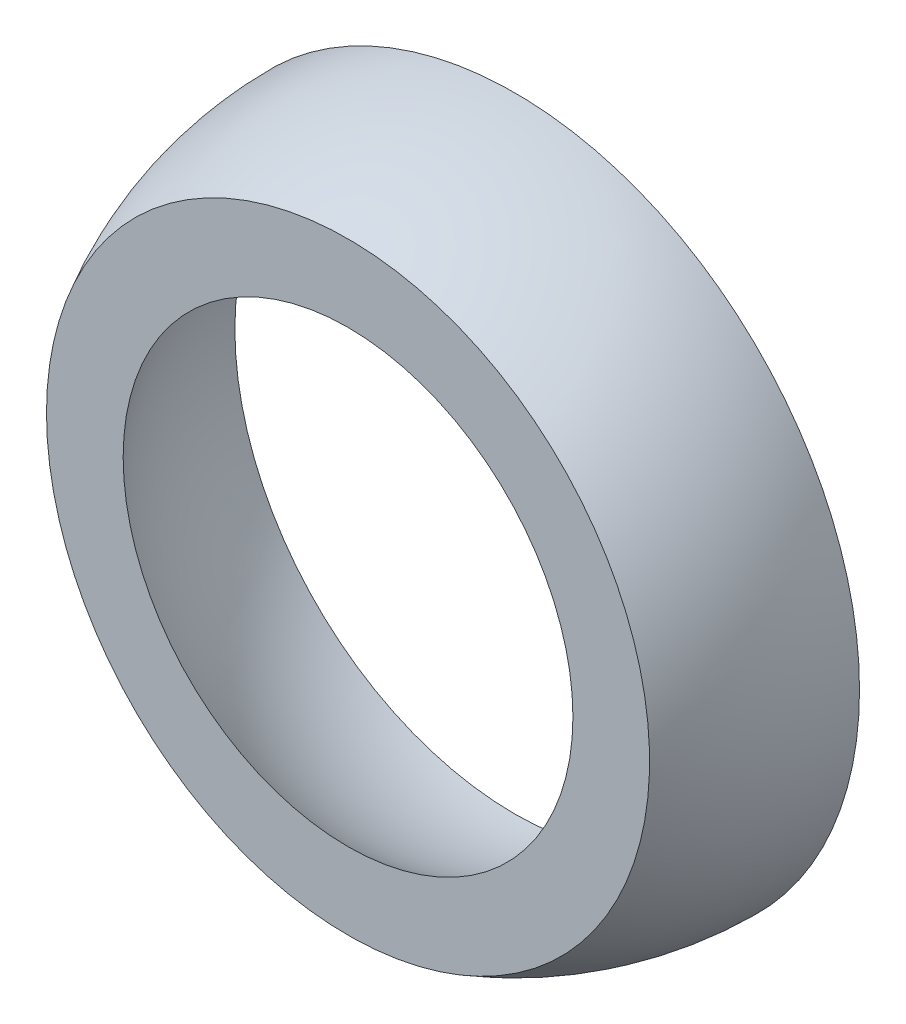
SolidWorks part; units mm, degrees
ref_plane "Plano frontal" through (0, 0, 0) normal (0, 0, 1) x (1, 0, 0)
ref_plane "Plano superior" through (0, 0, 0) normal (0, 1, 0) x (1, 0, 0)
ref_plane "Plano direito" through (0, 0, 0) normal (1, 0, 0) x (0, 0, -1)
sketch "Esboço1" plane through (0, 0, 0) normal (1, 0, 0) x (0, 0, -1)
  line L0 (-16, 0) -> (-13, 0)
  line L2 (0, 16) -> (0, 13)
  line L3 (-13, -9.1994) -> (-13, 13.9619) construction
  arc A0 (0, 13) -> (-13, 0) centre (0, 0) ccw
  arc A1 (-16, 0) -> (0, 16) centre (0, 0) cw
  dimension "D4" = 0
  dimension "D1" = 13
  dimension "D2" = 13
  dimension "D3" = 3
revolve "Revolução1" add sketch "Esboço1" angle 360 about L0
sketch "Esboço2" plane through (0, 0, 0) normal (1, 0, 0) x (0, 0, -1)
  line L1 (-7.746, 14) -> (-16, 14)
  line L2 (-7.746, 14) -> (-7.746, -14)
  line L3 (-7.746, -14) -> (-16, -14)
  line L4 (-16, 14) -> (-16, -14)
  arc A0 (0, 16) -> (0, -16) centre (0, 0) ccw construction
  point P4 (-7.746, 0)
  point P6 (0, 0)
  dimension "D1" = 28
extrude "Corte-extrusão1" cut sketch "Esboço2" against normal through all both and the other way through all
